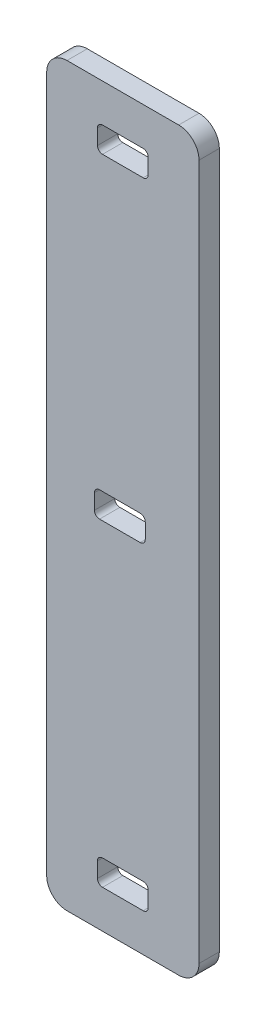
SolidWorks part; units mm, degrees
ref_plane "Plan de face" through (0, 0, 0) normal (0, 0, 1) x (1, 0, 0)
ref_plane "Plan de dessus" through (0, 0, 0) normal (0, 1, 0) x (1, 0, 0)
ref_plane "Plan de droite" through (0, 0, 0) normal (1, 0, 0) x (0, 0, -1)
sketch "Esquisse1" plane through (0, 0, 0) normal (0, 0, 1) x (1, 0, 0)
  line L1 (-11, -72.5) -> (11, -72.5)
  line L2 (-15, -68.5) -> (-15, 68.5)
  line L3 (-11, 72.5) -> (11, 72.5)
  line L4 (15, -68.5) -> (15, 68.5)
  line L5 (-15, -72.5) -> (15, 72.5) construction
  line L6 (-15, 72.5) -> (15, -72.5) construction
  arc A0 (-11, -72.5) -> (-15, -68.5) centre (-11, -68.5) cw
  arc A1 (11, -72.5) -> (15, -68.5) centre (11, -68.5) ccw
  arc A2 (-15, 68.5) -> (-11, 72.5) centre (-11, 68.5) cw
  arc A3 (11, 72.5) -> (15, 68.5) centre (11, 68.5) cw
  point P0 (0, 0)
  dimension "D3" = 4
  dimension "D1" = 145
  dimension "D2" = 30
extrude "Boss.-Extru.1" add sketch "Esquisse1" along normal blind 4
sketch "Esquisse2" plane through (0, 0, 4) normal (0, 0, 1) x (1, 0, 0)
  line L0 (11, 72.5) -> (-11, 72.5) construction
  line L1 (-4, -60) -> (4, -60)
  line L2 (-5, -61) -> (-5, -64)
  line L3 (-4, -65) -> (4, -65)
  line L4 (5, -61) -> (5, -64)
  line L5 (-5, -60) -> (5, -65) construction
  line L6 (-5, -65) -> (5, -60) construction
  line L7 (-4, 65) -> (4, 65)
  line L8 (-5, 64) -> (-5, 61)
  line L9 (-4, 60) -> (4, 60)
  line L10 (5, 64) -> (5, 61)
  line L11 (-5, 65) -> (5, 60) construction
  line L12 (-5, 60) -> (5, 65) construction
  line L13 (-11, -72.5) -> (11, -72.5) construction
  line L14 (-4.5876, 2.5) -> (3.4124, 2.5)
  line L15 (-15, 68.5) -> (-15, -68.5) construction
  line L16 (-5.5876, 1.5) -> (-5.5876, -1.5)
  line L17 (-4.5876, -2.5) -> (3.4124, -2.5)
  line L18 (4.4124, 1.5) -> (4.4124, -1.5)
  line L19 (-5.5876, 2.5) -> (4.4124, -2.5) construction
  line L20 (-5.5876, -2.5) -> (4.4124, 2.5) construction
  line L21 (-11, -72.5) -> (11, -72.5) construction
  arc A0 (-4, 65) -> (-5, 64) centre (-4, 64) ccw
  arc A1 (-5, 61) -> (-4, 60) centre (-4, 61) ccw
  arc A2 (4, 60) -> (5, 61) centre (4, 61) ccw
  arc A3 (4, 65) -> (5, 64) centre (4, 64) cw
  arc A4 (-4, -60) -> (-5, -61) centre (-4, -61) ccw
  arc A5 (-5, -64) -> (-4, -65) centre (-4, -64) ccw
  arc A6 (4, -65) -> (5, -64) centre (4, -64) ccw
  arc A7 (4, -60) -> (5, -61) centre (4, -61) cw
  arc A8 (-4.5876, 2.5) -> (-5.5876, 1.5) centre (-4.5876, 1.5) ccw
  arc A9 (-5.5876, -1.5) -> (-4.5876, -2.5) centre (-4.5876, -1.5) ccw
  arc A10 (3.4124, -2.5) -> (4.4124, -1.5) centre (3.4124, -1.5) ccw
  arc A11 (3.4124, 2.5) -> (4.4124, 1.5) centre (3.4124, 1.5) cw
  point P0 (0, -62.5)
  point P5 (0, 62.5)
  point P14 (0, 0)
  point P41 (-0.5876, 0)
  dimension "D9" = 1
  dimension "D10" = 1
  dimension "D11" = 1
  dimension "D1" = 7.5
  dimension "D2" = 7.5
  dimension "D3" = 5
  dimension "D4" = 5
  dimension "D5" = 10
  dimension "D6" = 15
  dimension "D7" = 10
  dimension "D8" = 15
  dimension "D12" = 72.5
  dimension "D13" = 5
extrude "Enlèv. mat.-Extru.1" cut sketch "Esquisse2" against normal through all
